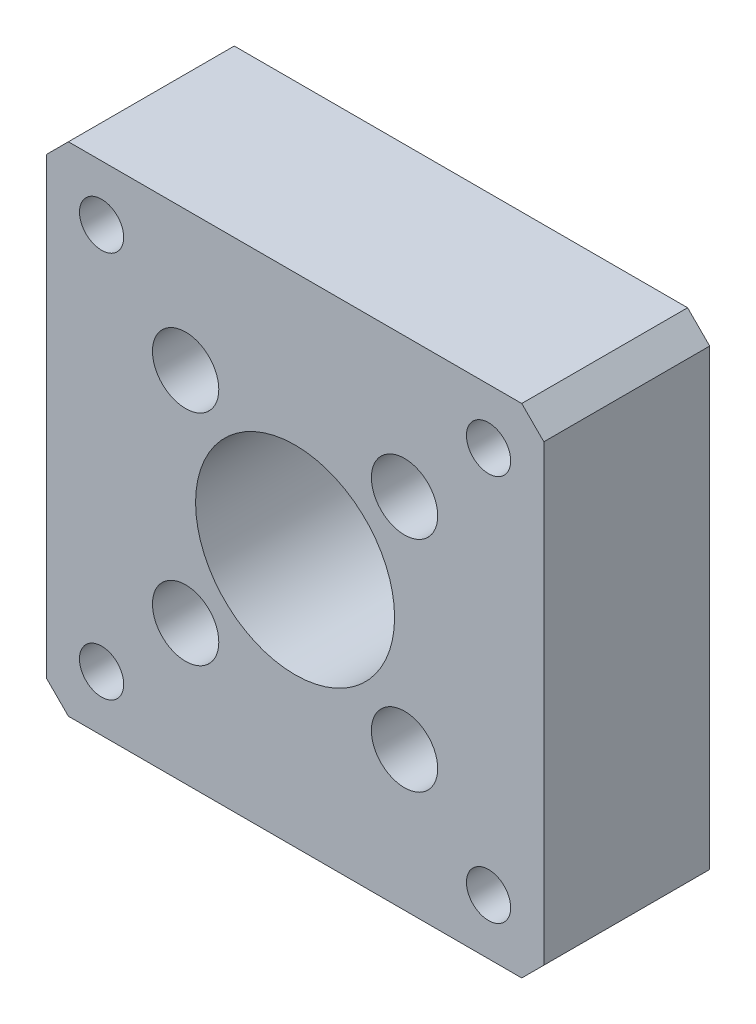
SolidWorks part; units mm, degrees
ref_plane "Front Plane" through (0, 0, 0) normal (0, 0, 1) x (1, 0, 0)
ref_plane "Top Plane" through (0, 0, 0) normal (0, 1, 0) x (1, 0, 0)
ref_plane "Right Plane" through (0, 0, 0) normal (1, 0, 0) x (0, 0, -1)
sketch "Sketch1" plane through (0, 0, 0) normal (0, 0, 1) x (1, 0, 0)
  line L1 (-22.5, 22.5) -> (22.5, 22.5)
  line L2 (-22.5, 22.5) -> (-22.5, -22.5)
  line L3 (-22.5, -22.5) -> (22.5, -22.5)
  line L4 (22.5, 22.5) -> (22.5, -22.5)
  line L5 (-22.5, 22.5) -> (22.5, -22.5) construction
  line L6 (-22.5, -22.5) -> (22.5, 22.5) construction
  circle A0 centre (0, 0) radius 9
  circle A1 centre (-17.5, 17.5) radius 2
  circle A2 centre (17.5, 17.5) radius 2
  circle A3 centre (17.5, -17.5) radius 2
  circle A4 centre (-17.5, -17.5) radius 2
  point P18 (0, 0)
  dimension "D1" = 18
  dimension "D4" = 4
  dimension "D2" = 45
  dimension "D3" = 45
  dimension "D6" = 35
  dimension "D5" = 4
extrude "Boss-Extrude1" add sketch "Sketch1" along normal blind 15
sketch "Sketch2" plane through (0, 0, 15) normal (0, 0, 1) x (1, 0, 0)
  line L0 (0, 0) -> (17.5497, 0) construction
  line L1 (0, 0) -> (9.8995, 9.8995) construction
  circle A0 centre (9.8995, 9.8995) radius 1.65
  circle A1 centre (9.8995, -9.8995) radius 1.65
  circle A2 centre (-9.8995, -9.8995) radius 1.65
  circle A3 centre (-9.8995, 9.8995) radius 1.65
  point P14 (0, 0)
  dimension "D2" = 3.3
  dimension "D1" = 45
  dimension "D3" = 14
  dimension "D4" = 4
extrude "Cut-Extrude1" cut sketch "Sketch2" against normal up to surface (15 mm away) up to face at (0, 0, 0)
sketch "Sketch3" plane through (0, 0, 15) normal (0, 0, 1) x (1, 0, 0)
  circle A0 centre (9.8995, 9.8995) radius 3
  circle A1 centre (9.8995, -9.8995) radius 3
  circle A2 centre (-9.8995, -9.8995) radius 3
  circle A3 centre (-9.8995, 9.8995) radius 3
  point P12 (0, 0)
  dimension "D1" = 6
  dimension "D2" = 4
extrude "Cut-Extrude2" cut sketch "Sketch3" against normal offset from surface (8 mm away) 7 up to face at (-8.2495, 9.8995, 0)
chamfer "Chamfer1" distance 2 angle 45 4 edges at (-22.5, -22.5, 7.5) (22.5, -22.5, 7.5) (22.5, 22.5, 7.5) (-22.5, 22.5, 7.5)
sketch "Sketch4" plane through (0, 0, 0) normal (0, 0, -1) x (-1, 0, 0)
  circle A0 centre (0, 0) radius 11.2
  dimension "D1" = 22.4
extrude "Cut-Extrude3" cut sketch "Sketch4" against normal blind 2
scale "Echelle1" scale about centroid uniform scaling yes scale factor 2
scale "Echelle2" scale about centroid uniform scaling yes scale factor 0.25
